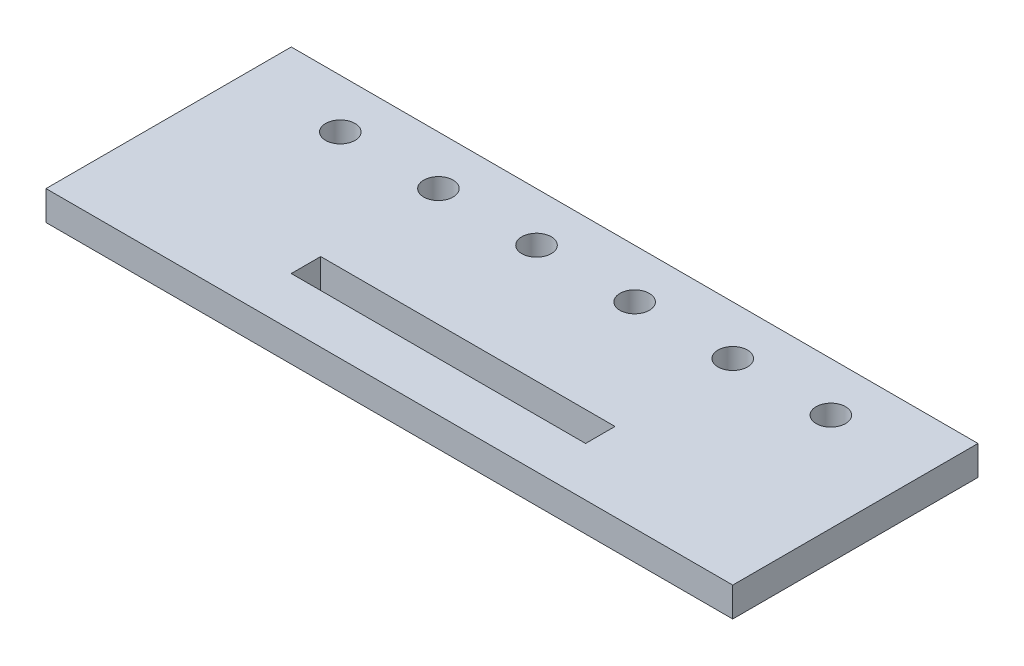
SolidWorks part; units mm, degrees
material "Maple"
ref_plane "Front Plane" through (0, 0, 0) normal (0, 0, 1) x (1, 0, 0)
ref_plane "Top Plane" through (0, 0, 0) normal (0, 1, 0) x (1, 0, 0)
ref_plane "Right Plane" through (0, 0, 0) normal (1, 0, 0) x (0, 0, -1)
sketch "Sketch1" plane through (0, 0, 0) normal (0, 1, 0) x (1, 0, 0)
  line L0 (-35, 0) -> (35, 0) construction
  line L5 (-35, 12.5) -> (35, 12.5)
  line L6 (-35, 12.5) -> (-35, -12.5)
  line L7 (-35, -12.5) -> (35, -12.5)
  line L8 (35, 12.5) -> (35, -12.5)
  line L9 (-35, 12.5) -> (35, -12.5) construction
  line L10 (-35, -12.5) -> (35, 12.5) construction
  line L11 (-25, 7.5) -> (-15, 7.5) construction
  line L12 (-15, 7.5) -> (-5, 7.5) construction
  line L13 (-5, 7.5) -> (5, 7.5) construction
  line L14 (5, 7.5) -> (15, 7.5) construction
  line L15 (15, 7.5) -> (25, 7.5) construction
  line L16 (25, 7.5) -> (25, 12.5) construction
  line L18 (-15, -4.5) -> (15, -4.5)
  line L19 (-15, -4.5) -> (-15, -7.5)
  line L20 (-15, -7.5) -> (15, -7.5)
  line L21 (15, -4.5) -> (15, -7.5)
  line L22 (-15, -4.5) -> (15, -7.5) construction
  line L23 (-15, -7.5) -> (15, -4.5) construction
  circle A0 centre (-25, 7.5) radius 1.5
  circle A2 centre (-15, 7.5) radius 1.5
  circle A3 centre (-5, 7.5) radius 1.5
  circle A4 centre (5, 7.5) radius 1.5
  circle A5 centre (15, 7.5) radius 1.5
  circle A6 centre (25, 7.5) radius 1.5
  point P0 (0, 0)
  point P10 (0, -6)
  point P26 (0, 0)
  dimension "D3" = 3
  dimension "D1" = 70
  dimension "D2" = 25
  dimension "D4" = 10
  dimension "D5" = 30
  dimension "D6" = 10
  dimension "D7" = 3
  dimension "D8" = 5
  dimension "D9" = 5
extrude "Boss-Extrude1" add sketch "Sketch1" along normal blind 3
